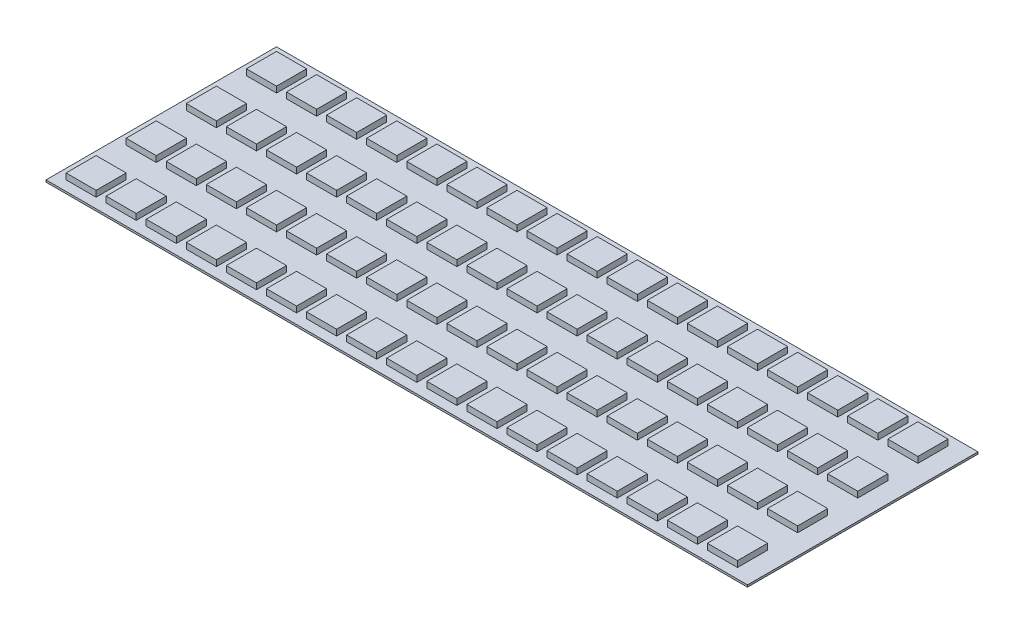
SolidWorks part; units mm, degrees
ref_plane "前基準面" through (0, 0, 0) normal (0, 0, 1) x (1, 0, 0)
ref_plane "上基準面" through (0, 0, 0) normal (0, 1, 0) x (1, 0, 0)
ref_plane "右基準面" through (0, 0, 0) normal (1, 0, 0) x (0, 0, -1)
sketch "草圖1" plane through (0, 0, 0) normal (0, 1, 0) x (1, 0, 0)
  line L0 (0, 0) -> (350, 0)
  line L1 (350, 0) -> (350, 115)
  line L2 (350, 115) -> (0, 115)
  line L3 (0, 115) -> (0, 0)
  dimension "D1" = 115
  dimension "D2" = 350
extrude "填料-伸長1" add sketch "草圖1" along normal blind 1
sketch "草圖2" plane through (0, 1, 0) normal (0, 1, 0) x (1, 0, 0)
  line L0 (5, 20) -> (5, 5)
  line L1 (5, 5) -> (20, 5)
  line L2 (20, 5) -> (20, 20)
  line L3 (20, 20) -> (5, 20)
  line L4 (0, 0) -> (350, 0) construction
  line L5 (0, 115) -> (0, 0) construction
  dimension "D1" = 15
  dimension "D2" = 15
  dimension "D3" = 5
  dimension "D4" = 5
extrude "填料-伸長2" add sketch "草圖2" along normal blind 3
pattern_linear "直線複製排列1" count 17 spacing 20 along (1, 0, 0) of "填料-伸長2"
pattern_linear "直線複製排列2" count 4 spacing 30 along (0, 0, -1) of "直線複製排列1", "填料-伸長2"
